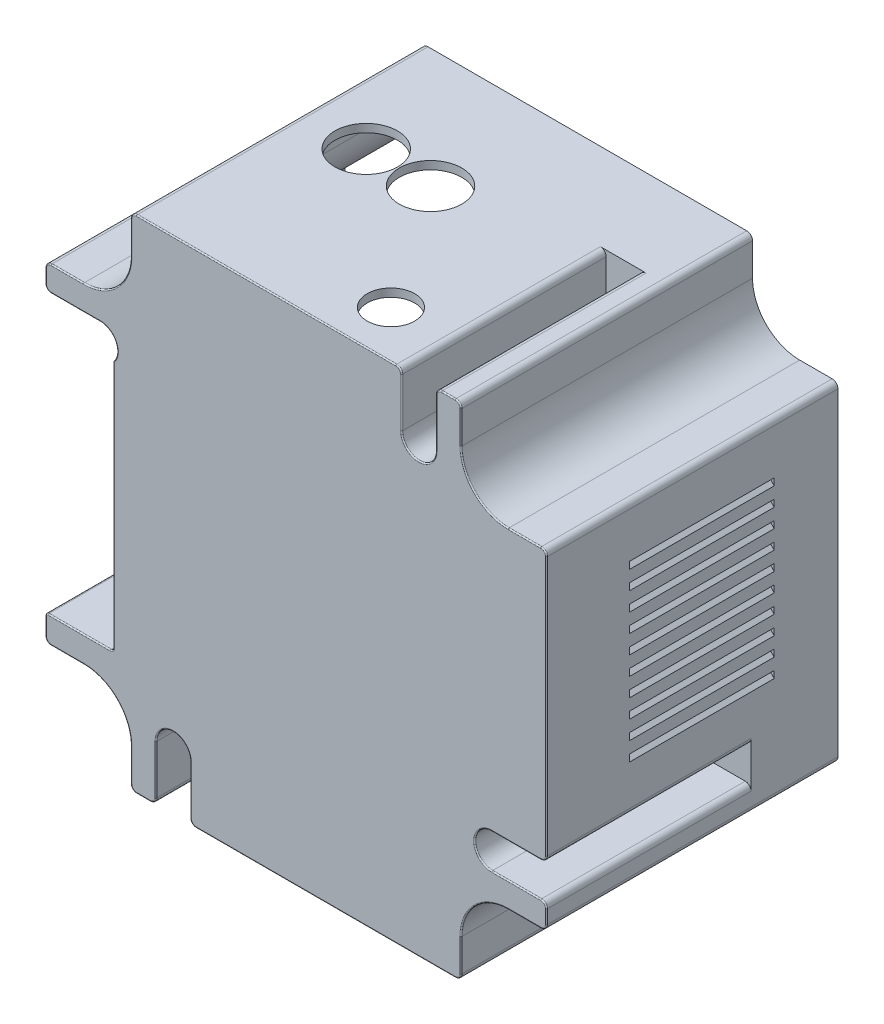
SolidWorks part; units mm, degrees
ref_plane "前视基准面" through (0, 0, 0) normal (0, 0, 1) x (1, 0, 0)
ref_plane "上视基准面" through (0, 0, 0) normal (0, 1, 0) x (1, 0, 0)
ref_plane "右视基准面" through (0, 0, 0) normal (1, 0, 0) x (0, 0, -1)
sketch "草图1" plane through (0, 0, 0) normal (0, 0, 1) x (1, 0, 0)
  line L0 (-27.5, 43.25) -> (27.5, 43.25)
  line L1 (-43.25, 27.5) -> (-43.25, 49.7664) construction
  line L5 (-42.25, 28.5) -> (-36.65, 28.5)
  line L6 (-28.5, 42.25) -> (-28.5, 36.65)
  line L7 (43.25, 27.5) -> (43.25, -27.5)
  line L8 (28.5, 42.25) -> (28.5, 36.65)
  line L9 (42.25, 28.5) -> (36.65, 28.5)
  line L10 (27.5, -43.25) -> (-27.5, -43.25)
  line L11 (42.25, -28.5) -> (36.65, -28.5)
  line L12 (28.5, -42.25) -> (28.5, -36.65)
  line L13 (-43.25, -27.5) -> (-43.25, 27.5)
  line L14 (-28.5, -42.25) -> (-28.5, -36.65)
  line L15 (-42.25, -28.5) -> (-36.65, -28.5)
  arc A0 (-27.5, 43.25) -> (-28.5, 42.25) centre (-27.5, 42.25) ccw
  arc A2 (-42.25, 28.5) -> (-43.25, 27.5) centre (-42.25, 27.5) ccw
  arc A12 (-28.5, 36.65) -> (-36.65, 28.5) centre (-36.65, 36.65) cw
  arc A13 (43.25, 27.5) -> (42.25, 28.5) centre (42.25, 27.5) ccw
  arc A14 (28.5, 42.25) -> (27.5, 43.25) centre (27.5, 42.25) ccw
  arc A15 (36.65, 28.5) -> (28.5, 36.65) centre (36.65, 36.65) cw
  arc A16 (27.5, -43.25) -> (28.5, -42.25) centre (27.5, -42.25) ccw
  arc A17 (42.25, -28.5) -> (43.25, -27.5) centre (42.25, -27.5) ccw
  arc A18 (28.5, -36.65) -> (36.65, -28.5) centre (36.65, -36.65) cw
  arc A19 (-43.25, -27.5) -> (-42.25, -28.5) centre (-42.25, -27.5) ccw
  arc A20 (-28.5, -42.25) -> (-27.5, -43.25) centre (-27.5, -42.25) ccw
  arc A21 (-36.65, -28.5) -> (-28.5, -36.65) centre (-36.65, -36.65) cw
  point P8 (0, 43.25)
  point P46 (0, 0)
  dimension "D2" = 1
  dimension "D1" = 43.25
  dimension "D3" = 43.25
  dimension "D4" = 55
  dimension "D5" = 5.6
extrude "凸台-拉伸1" add sketch "草图1" along normal blind 50.3
shell "抽壳1" thickness 1.4
ref_plane "基准面1" through (0, 0, 11) normal (0, 0, 1) x (1, 0, 0)
sketch "草图2" plane through (0, 0, 50.3) normal (0, 0, 1) x (1, 0, 0)
  line L0 (-21.1948, -33.8052) -> (-33.8052, 21.1948) construction
  line L1 (-21.1948, -33.8052) -> (33.8052, -21.1948) construction
  line L2 (-33.8052, 21.1948) -> (21.1948, 33.8052) construction
  line L3 (33.8052, -21.1948) -> (21.1948, 33.8052) construction
  line L4 (-21.1948, -33.8052) -> (21.1948, 33.8052) construction
  line L5 (-33.8052, 21.1948) -> (33.8052, -21.1948) construction
  line L6 (-33.8052, 24.1448) -> (-42.25, 24.1448)
  line L7 (-43.25, 27.5) -> (-43.25, -27.5) construction
  line L9 (-42.25, 18.2448) -> (-33.8052, 18.2448)
  line L20 (-43.25, 25.1448) -> (-43.25, 17.2448)
  line L30 (25.1448, 43.25) -> (17.2448, 43.25)
  line L31 (18.2448, 42.25) -> (18.2448, 33.8052)
  line L32 (24.1448, 33.8052) -> (24.1448, 42.25)
  line L33 (43.25, -25.1448) -> (43.25, -17.2448)
  line L34 (42.25, -18.2448) -> (33.8052, -18.2448)
  line L35 (33.8052, -24.1448) -> (42.25, -24.1448)
  line L36 (-25.1448, -43.25) -> (-17.2448, -43.25)
  line L37 (-18.2448, -42.25) -> (-18.2448, -33.8052)
  line L38 (-24.1448, -33.8052) -> (-24.1448, -42.25)
  arc A0 (-33.8052, 18.2448) -> (-33.8052, 24.1448) centre (-33.8052, 21.1948) ccw
  arc A7 (-42.25, 24.1448) -> (-43.25, 25.1448) centre (-42.25, 25.1448) cw
  arc A8 (-42.25, 18.2448) -> (-43.25, 17.2448) centre (-42.25, 17.2448) ccw
  arc A18 (18.2448, 42.25) -> (17.2448, 43.25) centre (17.2448, 42.25) ccw
  arc A19 (18.2448, 33.8052) -> (24.1448, 33.8052) centre (21.1948, 33.8052) ccw
  arc A20 (24.1448, 42.25) -> (25.1448, 43.25) centre (25.1448, 42.25) cw
  arc A21 (42.25, -18.2448) -> (43.25, -17.2448) centre (42.25, -17.2448) ccw
  arc A22 (33.8052, -18.2448) -> (33.8052, -24.1448) centre (33.8052, -21.1948) ccw
  arc A23 (42.25, -24.1448) -> (43.25, -25.1448) centre (42.25, -25.1448) cw
  arc A24 (-18.2448, -42.25) -> (-17.2448, -43.25) centre (-17.2448, -42.25) ccw
  arc A25 (-18.2448, -33.8052) -> (-24.1448, -33.8052) centre (-21.1948, -33.8052) ccw
  arc A26 (-24.1448, -42.25) -> (-25.1448, -43.25) centre (-25.1448, -42.25) cw
  point P1 (0, 0)
  point P30 (0, 0)
  point P47 (0.1012, -0.1012)
  point P48 (0, 0)
  dimension "D3" = 5.9
  dimension "D4" = 1
  dimension "D1" = 79.8
  dimension "D2" = 55
  dimension "D5" = 4
extrude "切除-拉伸1" cut sketch "草图2" against normal offset from surface (35.3 mm away) 4 up to plane "基准面1"
sketch "草图4" plane through (0, 0, 50.3) normal (0, 0, 1) x (1, 0, 0)
  line L0 (33.8052, -24.1448) -> (42.25, -24.1448) construction
  line L1 (-42.25, 18.2448) -> (-33.8052, 18.2448) construction
  line L2 (-33.8052, 24.1448) -> (-42.25, 24.1448) construction
  line L3 (-42.25, 18.2448) -> (-33.8052, 18.2448)
  line L4 (-33.8052, 24.1448) -> (-42.25, 24.1448)
  line L5 (42.25, -18.2448) -> (33.8052, -18.2448) construction
  line L6 (24.1448, 33.8052) -> (24.1448, 42.25) construction
  line L7 (33.8052, -24.1448) -> (42.25, -24.1448)
  line L8 (42.25, -18.2448) -> (33.8052, -18.2448)
  line L9 (24.1448, 33.8052) -> (24.1448, 42.25)
  line L10 (18.2448, 42.25) -> (18.2448, 33.8052) construction
  line L11 (18.2448, 42.25) -> (18.2448, 33.8052)
  line L12 (-18.2448, -42.25) -> (-18.2448, -33.8052) construction
  line L13 (-24.1448, -33.8052) -> (-24.1448, -42.25) construction
  line L14 (-18.2448, -42.25) -> (-18.2448, -33.8052)
  line L15 (-24.1448, -33.8052) -> (-24.1448, -42.25)
  arc A0 (-33.8052, 18.2448) -> (-33.8052, 24.1448) centre (-33.8052, 21.1948) ccw construction
  arc A1 (-33.8052, 18.2448) -> (-33.8052, 24.1448) centre (-33.8052, 21.1948) ccw
  arc A2 (33.8052, -18.2448) -> (33.8052, -24.1448) centre (33.8052, -21.1948) ccw construction
  arc A3 (18.2448, 33.8052) -> (24.1448, 33.8052) centre (21.1948, 33.8052) ccw construction
  arc A4 (33.8052, -18.2448) -> (33.8052, -24.1448) centre (33.8052, -21.1948) ccw
  arc A5 (18.2448, 33.8052) -> (24.1448, 33.8052) centre (21.1948, 33.8052) ccw
  arc A6 (-18.2448, -33.8052) -> (-24.1448, -33.8052) centre (-21.1948, -33.8052) ccw construction
  arc A7 (-18.2448, -33.8052) -> (-24.1448, -33.8052) centre (-21.1948, -33.8052) ccw
extrude "拉伸-薄壁2" add sketch "草图4" against normal up to surface (35.3 mm away) thin
sketch "草图5" plane through (0, 0, 15) normal (0, 0, -1) x (-1, 0, 0)
  line L0 (41.85, 16.8448) -> (33.8052, 16.8448) construction
  line L1 (33.8052, 25.5448) -> (41.85, 25.5448) construction
  line L2 (41.85, 16.8448) -> (33.8052, 16.8448)
  line L3 (33.8052, 25.5448) -> (41.85, 25.5448)
  line L4 (41.85, 25.5448) -> (41.85, 16.8448)
  line L68 (16.8448, -41.85) -> (16.8448, -33.8052)
  line L69 (25.5448, -33.8052) -> (25.5448, -41.85)
  line L70 (25.5448, -41.85) -> (16.8448, -41.85)
  line L71 (-41.85, -16.8448) -> (-33.8052, -16.8448)
  line L72 (-33.8052, -25.5448) -> (-41.85, -25.5448)
  line L73 (-41.85, -25.5448) -> (-41.85, -16.8448)
  line L74 (-16.8448, 41.85) -> (-16.8448, 33.8052)
  line L75 (-25.5448, 33.8052) -> (-25.5448, 41.85)
  line L76 (-25.5448, 41.85) -> (-16.8448, 41.85)
  line L77 (0, 0) -> (33.8052, 16.8448) construction
  arc A0 (33.8052, 25.5448) -> (33.8052, 16.8448) centre (33.8052, 21.1948) ccw construction
  arc A1 (33.8052, 25.5448) -> (33.8052, 16.8448) centre (33.8052, 21.1948) ccw
  circle A5 centre (33.8052, 21.1948) radius 1.65
  arc A39 (25.5448, -33.8052) -> (16.8448, -33.8052) centre (21.1948, -33.8052) ccw
  circle A40 centre (21.1948, -33.8052) radius 1.65
  arc A41 (-33.8052, -25.5448) -> (-33.8052, -16.8448) centre (-33.8052, -21.1948) ccw
  circle A42 centre (-33.8052, -21.1948) radius 1.65
  arc A43 (-25.5448, 33.8052) -> (-16.8448, 33.8052) centre (-21.1948, 33.8052) ccw
  circle A44 centre (-21.1948, 33.8052) radius 1.65
  dimension "D1" = 3.3
  dimension "D3" = 37.7695
  dimension "D2" = 4
extrude "凸台-拉伸2" add sketch "草图5" along normal up to surface (4 mm away) up to plane "基准面1"
sketch "草图6" plane through (0, 0, 11) normal (0, 0, -1) x (-1, 0, 0)
  line L1 (-25.5, -30.5) -> (25.5, -30.5)
  line L2 (-30.5, -25.5) -> (-30.5, 25.5)
  line L3 (-25.5, 30.5) -> (25.5, 30.5)
  line L4 (30.5, -25.5) -> (30.5, 25.5)
  line L5 (-30.5, -30.5) -> (30.5, 30.5) construction
  line L6 (-30.5, 30.5) -> (30.5, -30.5) construction
  arc A0 (-25.5, -30.5) -> (-30.5, -25.5) centre (-25.5, -25.5) cw
  arc A1 (25.5, -30.5) -> (30.5, -25.5) centre (25.5, -25.5) ccw
  arc A2 (25.5, 30.5) -> (30.5, 25.5) centre (25.5, 25.5) cw
  arc A3 (-30.5, 25.5) -> (-25.5, 30.5) centre (-25.5, 25.5) cw
  point P0 (0, 0)
  dimension "D2" = 5
  dimension "D1" = 61
extrude "切除-拉伸2" cut sketch "草图6" against normal blind 25
sketch "草图7" plane through (0, 0, 50.3) normal (0, 0, 1) x (1, 0, 0)
  line L0 (-42.25, -28.5) -> (-36.65, -28.5) construction
  line L5 (-43.25, 17.2448) -> (-43.25, -27.5) construction
  line L6 (-43.25, 20.5) -> (-30.45, 20.5)
  line L7 (-43.25, 20.5) -> (-43.25, -24)
  line L8 (-43.25, -24) -> (-30.45, -24)
  line L9 (-30.45, 20.5) -> (-30.45, -24)
  dimension "D1" = 4.5
  dimension "D2" = 49
  dimension "D3" = 12.8
extrude "切除-拉伸3" cut sketch "草图7" against normal offset from surface (34.3 mm away) 16 up to face at (0, 0, 0)
sketch "草图8" plane through (0, 43.25, 0) normal (0, 1, 0) x (1, 0, 0)
  line L0 (-28.5, -50.3) -> (-28.5, 0) construction
  line L2 (27.5, 0) -> (-27.5, 0) construction
  line L3 (18.2448, -15) -> (18.2448, -50.3) construction
  line L5 (17.2448, -50.3) -> (-27.5, -50.3) construction
  circle A0 centre (-6.47, -20.6) radius 5.4
  circle A1 centre (-17.57, -20.6) radius 5.4
  circle A2 centre (8.2448, -42.15) radius 5.65 construction
  circle A3 centre (8.2448, -42.15) radius 4.1
  dimension "D1" = 10.8
  dimension "D2" = 10.8
  dimension "D6" = 8.2
  dimension "D7" = 11.3
  dimension "D8" = 2.5
  dimension "D3" = 10.93
  dimension "D4" = 11.1
  dimension "D5" = 20.6
  dimension "D9" = 10
extrude "切除-拉伸4" cut sketch "草图8" against normal up to next contours A0
sketch "草图9" plane through (0, -24, 0) normal (0, 1, 0) x (1, 0, 0)
  line L0 (-43.25, -14.9) -> (-43.25, -16)
  line L2 (-43.25, -16) -> (-31.55, -16)
  line L3 (-31.55, -16) -> (-31.55, -50.3)
  line L4 (-36.65, -50.3) -> (-28.5, -50.3) construction
  line L6 (-31.55, -50.3) -> (-30.45, -50.3)
  line L8 (-30.45, -50.3) -> (-30.45, -14.9)
  line L10 (-30.45, -14.9) -> (-43.25, -14.9)
  line L12 (-30.45, -36) -> (-30.45, -50.3) construction
  dimension "D1" = 1.1
extrude "凸台-拉伸3" add sketch "草图9" along normal up to surface (44.5 mm away) up to face at (-30.6294, 20.5, 34.1)
sketch "草图10" plane through (0, -24, 0) normal (0, 1, 0) x (1, 0, 0)
  line L0 (-30.45, -14.9) -> (-41.85, -14.9) construction
  line L1 (-30.45, -48.9) -> (-43.25, -48.9)
  line L2 (-30.45, -48.9) -> (-30.45, -14.9)
  line L3 (-30.45, -14.9) -> (-43.25, -14.9)
  line L4 (-43.25, -48.9) -> (-43.25, -14.9)
  line L5 (-43.25, -16) -> (-43.25, -50.3) construction
extrude "凸台-拉伸5" add sketch "草图10" against normal blind 1.1
sketch "草图11" plane through (0, 0, 15) normal (0, 0, 1) x (1, 0, 0)
  line L0 (-42.25, 18.2448) -> (-33.8052, 18.2448) construction
  line L1 (-33.8052, 24.1448) -> (-42.25, 24.1448) construction
  line L2 (-43.25, 25.1448) -> (-43.25, 17.2448) construction
  line L3 (-42.25, 18.2448) -> (-33.8052, 18.2448)
  line L4 (-33.8052, 24.1448) -> (-42.25, 24.1448)
  line L5 (-43.25, 25.1448) -> (-43.25, 17.2448)
  arc A0 (-33.8052, 18.2448) -> (-33.8052, 24.1448) centre (-33.8052, 21.1948) ccw construction
  arc A1 (-43.25, 25.1448) -> (-42.25, 24.1448) centre (-42.25, 25.1448) ccw construction
  arc A2 (-42.25, 18.2448) -> (-43.25, 17.2448) centre (-42.25, 17.2448) ccw construction
  arc A3 (-33.8052, 18.2448) -> (-33.8052, 24.1448) centre (-33.8052, 21.1948) ccw
  arc A4 (-43.25, 25.1448) -> (-42.25, 24.1448) centre (-42.25, 25.1448) ccw
  arc A5 (-42.25, 18.2448) -> (-43.25, 17.2448) centre (-42.25, 17.2448) ccw
extrude "切除-拉伸5" cut sketch "草图11" along normal up to surface (35.3 mm away) up to face at (-0.4049, -1.2295, 50.3)
sketch "草图13" plane through (0, 0, 15) normal (0, 0, 1) x (1, 0, 0)
  circle A0 centre (-33.8052, 21.1948) radius 1.65
  circle A1 centre (-33.8052, 21.1948) radius 1.65 construction
extrude "切除-拉伸7" cut sketch "草图13" against normal through all
sketch "草图12" plane through (-31.55, 0, 0) normal (-1, 0, 0) x (0, 0, 1)
  line L0 (0, 27.5) -> (0, -27.5) construction
  line L1 (32.8, 19.5) -> (47.3, 19.5)
  line L2 (32.8, 19.5) -> (32.8, 7.2)
  line L3 (32.8, 7.2) -> (47.3, 7.2)
  line L4 (47.3, 19.5) -> (47.3, 7.2)
  line L5 (32.8, 3.5) -> (47.3, 3.5)
  line L6 (32.8, 3.5) -> (32.8, -8.8)
  line L7 (32.8, -8.8) -> (47.3, -8.8)
  line L8 (47.3, 3.5) -> (47.3, -8.8)
  line L17 (50.3, 28.5) -> (0, 28.5) construction
  line L19 (34.6, -18.9) -> (34.6, -13.2) construction
  line L20 (32.8, -18.9) -> (32.8, -13.2)
  line L21 (36.4, -18.9) -> (36.4, -13.2)
  line L22 (22, -15.3) -> (22, -9.6) construction
  line L23 (20.2, -15.3) -> (20.2, -9.6)
  line L24 (23.8, -15.3) -> (23.8, -9.6)
  arc A0 (32.8, -18.9) -> (36.4, -18.9) centre (34.6, -18.9) ccw
  arc A1 (36.4, -13.2) -> (32.8, -13.2) centre (34.6, -13.2) ccw
  arc A2 (20.2, -15.3) -> (23.8, -15.3) centre (22, -15.3) ccw
  arc A3 (23.8, -9.6) -> (20.2, -9.6) centre (22, -9.6) ccw
  point P8 (22, -12.45)
  point P12 (34.6, -16.05)
  point P29 (34.6, -11.4)
  point P30 (34.6, -20.7)
  point P36 (22, -7.8)
  point P37 (22, -17.1)
  dimension "D1" = 12.3
  dimension "D2" = 14.5
  dimension "D3" = 32.8
  dimension "D4" = 2.6
  dimension "D5" = 9.3
  dimension "D6" = 3.6
  dimension "D7" = 20.2
  dimension "D8" = 16
  dimension "D9" = 36.3
  dimension "D10" = 9
  dimension "D12" = 9.3
  dimension "D13" = 3.6
  dimension "D14" = 32.8
extrude "切除-拉伸6" cut sketch "草图12" against normal up to next
fillet "圆角1" radius 0.5 2 edges at (-31.55, -24, 33.15) (-43.25, -24, 33.15)
fillet "圆角3" radius 0.2 50 edges at (-31.6964, -23.8536, 50.3) (-31.55, -2.1035, 50.3) (-31.13, 22.4383, 50.3) (-38.0276, 24.1448, 50.3) (-42.9571, 24.4377, 50.3) (-43.25, 26.3224, 50.3) (-42.9571, 28.2071, 50.3) (-39.45, 28.5, 50.3) (-30.8871, 30.8871, 50.3) (-28.5, 39.45, 50.3) (-28.2071, 42.9571, 50.3) (-5.1276, 43.25, 50.3) (17.952, 42.9571, 50.3) (18.2448, 38.0276, 50.3) (21.1948, 30.8552, 50.3) (24.1448, 38.0276, 50.3) (24.4377, 42.9571, 50.3) (26.3224, 43.25, 50.3) (28.2071, 42.9571, 50.3) (28.5, 39.45, 50.3) (30.8871, 30.8871, 50.3) (39.45, 28.5, 50.3) (42.9571, 28.2071, 50.3) (43.25, 5.1276, 50.3) (42.9571, -17.952, 50.3) (38.0276, -18.2448, 50.3) (30.8552, -21.1948, 50.3) (38.0276, -24.1448, 50.3) (42.9571, -24.4377, 50.3) (43.25, -26.3224, 50.3) (42.9571, -28.2071, 50.3) (39.45, -28.5, 50.3) (30.8871, -30.8871, 50.3) (28.5, -39.45, 50.3) (28.2071, -42.9571, 50.3) (5.1276, -43.25, 50.3) (-17.952, -42.9571, 50.3) (-18.2448, -38.0276, 50.3) (-21.1948, -30.8552, 50.3) (-24.1448, -38.0276, 50.3) (-24.4377, -42.9571, 50.3) (-26.3224, -43.25, 50.3) (-28.2071, -42.9571, 50.3) (-28.5, -39.45, 50.3) (-30.8871, -30.8871, 50.3) (-39.45, -28.5, 50.3) (-42.9571, -28.2071, 50.3) (-43.25, -26, 50.3) (-43.1036, -24.1464, 50.3) (-37.4, -24, 50.3)
sketch "草图14" plane through (0, 0, 11) normal (0, 0, 1) x (1, 0, 0)
  line L0 (41.85, 21.1) -> (43.25, 19.7)
  line L1 (41.85, 21.1) -> (41.85, 19.9)
  line L2 (43.25, 19.7) -> (43.25, 18.5)
  line L3 (41.85, 19.9) -> (43.25, 18.5)
  line L4 (41.85, -16.8448) -> (41.85, 27.1) construction
  line L5 (43.25, 27.5) -> (43.25, -17.2448) construction
  line L6 (41.85, 27.1) -> (36.65, 27.1) construction
  line L7 (41.85, 17.9) -> (43.25, 16.5)
  line L8 (41.85, 17.9) -> (41.85, 16.7)
  line L9 (43.25, 16.5) -> (43.25, 15.3)
  line L10 (41.85, 16.7) -> (43.25, 15.3)
  line L11 (41.85, 14.7) -> (43.25, 13.3)
  line L12 (41.85, 14.7) -> (41.85, 13.5)
  line L13 (43.25, 13.3) -> (43.25, 12.1)
  line L14 (41.85, 13.5) -> (43.25, 12.1)
  line L15 (41.85, 11.5) -> (43.25, 10.1)
  line L16 (41.85, 11.5) -> (41.85, 10.3)
  line L17 (43.25, 10.1) -> (43.25, 8.9)
  line L18 (41.85, 10.3) -> (43.25, 8.9)
  line L19 (41.85, 8.3) -> (43.25, 6.9)
  line L20 (41.85, 8.3) -> (41.85, 7.1)
  line L21 (43.25, 6.9) -> (43.25, 5.7)
  line L22 (41.85, 7.1) -> (43.25, 5.7)
  line L23 (41.85, 5.1) -> (43.25, 3.7)
  line L24 (41.85, 5.1) -> (41.85, 3.9)
  line L25 (43.25, 3.7) -> (43.25, 2.5)
  line L26 (41.85, 3.9) -> (43.25, 2.5)
  line L27 (41.85, 1.9) -> (43.25, 0.5)
  line L28 (41.85, 1.9) -> (41.85, 0.7)
  line L29 (43.25, 0.5) -> (43.25, -0.7)
  line L30 (41.85, 0.7) -> (43.25, -0.7)
  line L31 (41.85, -1.3) -> (43.25, -2.7)
  line L32 (41.85, -1.3) -> (41.85, -2.5)
  line L33 (43.25, -2.7) -> (43.25, -3.9)
  line L34 (41.85, -2.5) -> (43.25, -3.9)
  line L35 (41.85, -4.5) -> (43.25, -5.9)
  line L36 (41.85, -4.5) -> (41.85, -5.7)
  line L37 (43.25, -5.9) -> (43.25, -7.1)
  line L38 (41.85, -5.7) -> (43.25, -7.1)
  line L39 (41.85, -7.7) -> (43.25, -9.1)
  line L40 (41.85, -7.7) -> (41.85, -8.9)
  line L41 (43.25, -9.1) -> (43.25, -10.3)
  line L42 (41.85, -8.9) -> (43.25, -10.3)
  dimension "D1" = 1.2
  dimension "D2" = 45
  dimension "D3" = 6
  dimension "D4" = 10
extrude "切除-拉伸8" cut sketch "草图14" along normal blind 25
